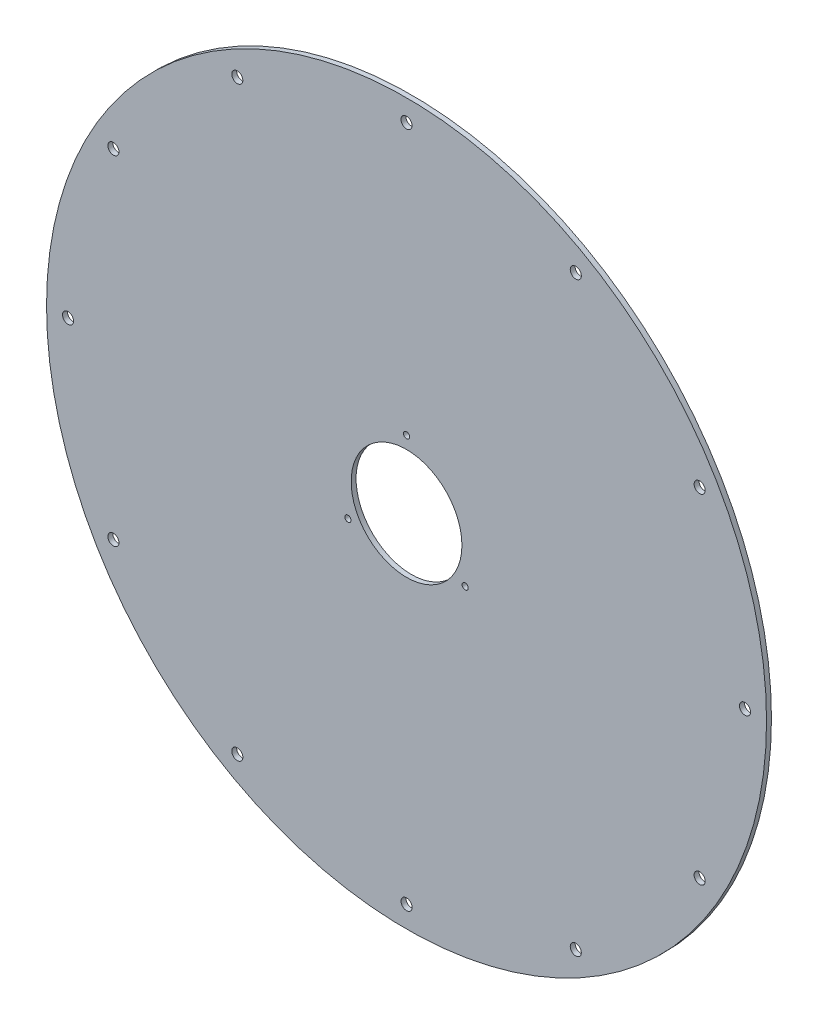
SolidWorks part; units mm, degrees
material "ASTM A36 Steel"
ref_plane "Front Plane" through (0, 0, 0) normal (0, 0, 1) x (1, 0, 0)
ref_plane "Top Plane" through (0, 0, 0) normal (0, 1, 0) x (1, 0, 0)
ref_plane "Right Plane" through (0, 0, 0) normal (1, 0, 0) x (0, 0, -1)
sketch "Sketch1" plane through (0, 0, 0) normal (0, 0, 1) x (1, 0, 0)
  circle A0 centre (0, 0) radius 292.5
  circle A1 centre (0, 0) radius 45
  dimension "D1" = 585
  dimension "D2" = 90
extrude "Boss-Extrude1" add sketch "Sketch1" along normal blind 4
sketch "Sketch2" plane through (0, 0, 4) normal (0, 0, 1) x (1, 0, 0)
  circle A0 centre (0, 275) radius 4.5
  dimension "D1" = 9
  dimension "D2" = 275
extrude "Cut-Extrude1" cut sketch "Sketch2" against normal through all
pattern_circular "CirPattern1" count 12 every 30 about axis through (0, 0, 0) along (0, 0, 1) of "Cut-Extrude1"
sketch "Sketch3" plane through (0, 0, 4) normal (0, 0, 1) x (1, 0, 0)
  circle A0 centre (0, 183) radius 4
  dimension "D1" = 8
  dimension "D2" = 183
extrude "Boss-Extrude2" [suppressed] add sketch "Sketch3" along normal blind 25
pattern_circular "CirPattern2" [suppressed] count 12 every 30
hole_wizard "M6x1.0 Tapped Hole1" positions "Sketch7" profile "Sketch6" tap size "M6x1.0" standard "ANSI Metric"
sketch "Sketch7" plane through (0, 0, 0) normal (0, 0, -1) x (-1, 0, 0)
  point P0 (0, 55)
  dimension "D1" = 55
sketch "Sketch6" plane through (0, 55, 0) normal (1, 0, 0) x (0, 1, 0)
  line L0 (0, 0) -> (0, 16.5022)
  line L1 (0, 16.5022) -> (2.5, 15)
  line L2 (2.5, 15) -> (2.5, 0)
  line L5 (2.5, 0) -> (0, 0)
  line L10 (0, 16.5022) -> (-2.5, 15) construction
  line L11 (0, -6.35) -> (0, 107.95) construction
  dimension "Tap Drill Dia." = 5
  dimension "Tap Drill Depth" = 15
  dimension "Drill Angle" = 118
cosmetic thread "Hole Thread1" parameters "D1"=4, "D2"=6
pattern_circular "CirPattern3" count 3 every 120 about axis through (0, 0, 0) along (0, 0, 1) of "M6x1.0 Tapped Hole1"
